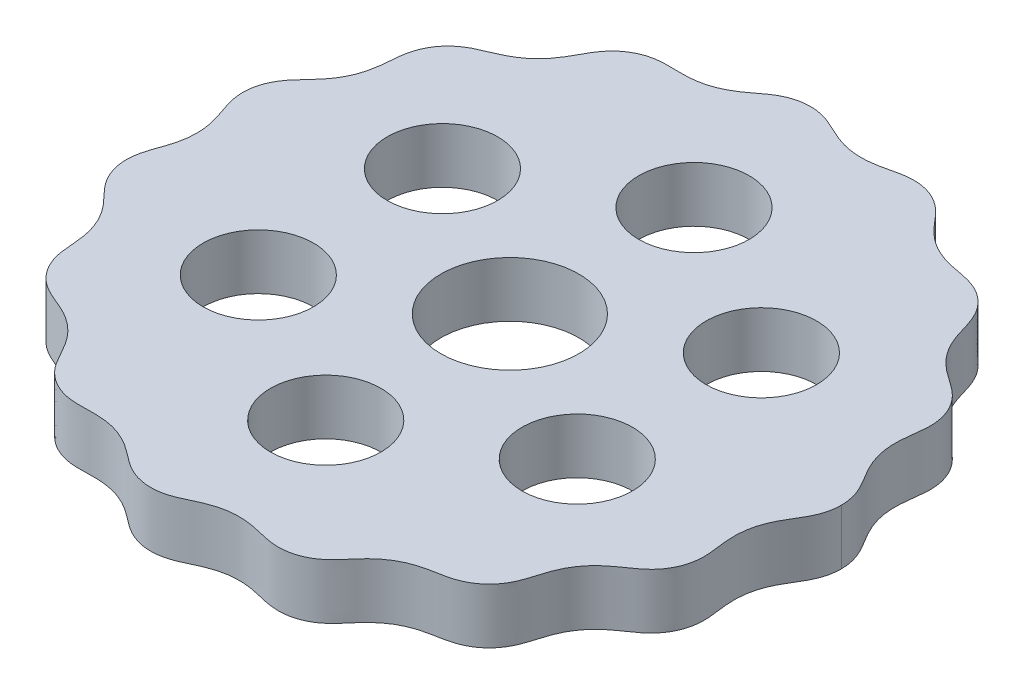
SolidWorks part; units mm, degrees
ref_plane "Front Plane" through (0, 0, 0) normal (0, 0, 1) x (1, 0, 0)
ref_plane "Top Plane" through (0, 0, 0) normal (0, 1, 0) x (1, 0, 0)
ref_plane "Right Plane" through (0, 0, 0) normal (1, 0, 0) x (0, 0, -1)
sketch "Sketch3" plane through (0, 0, 0) normal (0, 1, 0) x (1, 0, 0)
  line L0 (-55, 0) -> (55, 0) construction
  spline S2 degree 4 poles (-35, 0) (-35, -0.0358) (-35.0006, -0.1075) (-35.0034, -0.2568) (-35.0108, -0.4216) (-35.0218, -0.5882) (-35.0365, -0.7567) (-35.0593, -0.9658) (-35.104, -1.2906) (-35.1852, -1.7284) (-35.3211, -2.2743) (-35.5114, -2.8829) (-35.7441, -3.5419) (-35.9992, -4.258) (-36.256, -5.1614) (-36.3903, -6.2748) (-36.277, -7.5121) (-35.8687, -8.6952) (-35.2773, -9.6694) (-34.5543, -10.5199) (-33.7836, -11.2989) (-32.9858, -12.2016) (-32.2646, -13.303) (-31.7377, -14.5286) (-31.4262, -15.8454) (-31.2991, -17.2726) (-31.2161, -18.7053) (-30.8161, -20.1006) (-30.0732, -21.3418) (-29.1744, -22.2504) (-28.1724, -22.8961) (-27.1276, -23.3559) (-26.1086, -23.7587) (-25.0498, -24.278) (-23.9897, -24.9979) (-23.0387, -25.9222) (-22.2349, -27.0329) (-21.57, -28.2819) (-20.9001, -29.5134) (-19.9625, -30.5741) (-18.7952, -31.3663) (-17.5956, -31.8107) (-16.4147, -31.9743) (-15.2812, -31.959) (-14.2035, -31.9175) (-13.0422, -31.968) (-11.7833, -32.2012) (-10.5313, -32.6697) (-9.484, -33.2925) (-8.6483, -33.9206) (-7.824, -34.5602) (-6.9633, -35.1551) (-5.8447, -35.655) (-4.4715, -35.8938) (-3.1871, -35.8055) (-2.026, -35.4617) (-0.9923, -34.9762) (-0.0227, -34.5029) (1.0531, -34.0876) (2.2996, -33.7945) (3.6433, -33.7224) (5.0385, -33.8989) (6.246, -34.2125) (7.2644, -34.4441) (8.3052, -34.5433) (9.3521, -34.4822) (10.5168, -34.1673) (11.6593, -33.5372) (12.5907, -32.7091) (13.341, -31.8149) (14.0543, -30.9824) (14.885, -30.183) (15.9219, -29.4318) (16.9904, -28.9178) (18.0263, -28.6023) (18.918, -28.4136) (19.5788, -28.294) (20.4038, -28.1355) (21.3777, -27.8617) (22.444, -27.3351) (23.4837, -26.4602) (24.2541, -25.4059) (24.7506, -24.2626) (25.0639, -23.1466) (25.3786, -22.114) (25.8131, -21.0649) (26.4604, -19.9607) (27.3438, -18.9326) (28.3229, -18.1436) (29.2182, -17.5418) (30.0287, -16.9727) (30.7971, -16.3286) (31.5499, -15.4136) (32.138, -14.1887) (32.4089, -12.902) (32.389, -11.6377) (32.2136, -10.4744) (32.0853, -9.3852) (32.0701, -8.4106) (32.1519, -7.5639) (32.3146, -6.756) (32.5488, -5.9926) (32.8579, -5.2665) (33.2246, -4.5794) (33.5887, -3.9735) (33.9236, -3.4333) (34.2476, -2.8753) (34.5352, -2.2866) (34.722, -1.7814) (34.8335, -1.3753) (34.8947, -1.0872) (34.9248, -0.9216) (34.9499, -0.7552) (34.9676, -0.6083) (34.9796, -0.4838) (34.9875, -0.3802) (34.9925, -0.2949) (34.9973, -0.1832) (34.9994, -0.0895) (35, -0.0358) (35, 0) knots 0.07237 0.07237 0.07237 0.07237 0.07237 0.073615 0.074861 0.076106 0.077352 0.078597 0.079843 0.082334 0.087049 0.091763 0.096478 0.101193 0.107725 0.114257 0.124215 0.134174 0.144133 0.15093 0.157727 0.167143 0.176558 0.186521 0.196482 0.206428 0.216375 0.228908 0.238867 0.248826 0.258784 0.266347 0.27391 0.282559 0.291208 0.301173 0.311645 0.3216 0.331555 0.343059 0.353018 0.362977 0.372935 0.380513 0.388091 0.396475 0.404859 0.414823 0.425824 0.43578 0.440758 0.445737 0.45671 0.466668 0.476627 0.486585 0.494428 0.502271 0.510391 0.51851 0.528475 0.540003 0.54996 0.559918 0.565389 0.570861 0.580819 0.590778 0.600736 0.609095 0.617453 0.625308 0.633162 0.643126 0.655188 0.660155 0.665121 0.670088 0.675054 0.685012 0.69497 0.704929 0.714887 0.72326 0.731632 0.739222 0.746812 0.756777 0.769366 0.779036 0.78387 0.788705 0.798662 0.808621 0.81858 0.828538 0.837175 0.845812 0.853389 0.860965 0.865947 0.870929 0.877739 0.88455 0.889251 0.893953 0.898654 0.903356 0.908335 0.913314 0.914559 0.915803 0.917048 0.918293 0.919538 0.92016 0.920783 0.921405 0.922028 0.923272 0.923272 0.923272 0.923272 0.923272
  spline S3 degree 4 poles (-35, 0) (-35, 0.0358) (-35.0006, 0.1075) (-35.0034, 0.2568) (-35.0108, 0.4216) (-35.0218, 0.5882) (-35.0365, 0.7567) (-35.0593, 0.9658) (-35.104, 1.2906) (-35.1852, 1.7284) (-35.3211, 2.2743) (-35.5114, 2.8829) (-35.7441, 3.5419) (-35.9992, 4.258) (-36.256, 5.1614) (-36.3903, 6.2748) (-36.277, 7.5121) (-35.8687, 8.6952) (-35.2773, 9.6694) (-34.5543, 10.5199) (-33.7836, 11.2989) (-32.9858, 12.2016) (-32.2646, 13.303) (-31.7377, 14.5286) (-31.4262, 15.8454) (-31.2991, 17.2726) (-31.2161, 18.7053) (-30.8161, 20.1006) (-30.0732, 21.3418) (-29.1744, 22.2504) (-28.1724, 22.8961) (-27.1276, 23.3559) (-26.1086, 23.7587) (-25.0498, 24.278) (-23.9897, 24.9979) (-23.0387, 25.9222) (-22.2349, 27.0329) (-21.57, 28.2819) (-20.9001, 29.5134) (-19.9625, 30.5741) (-18.7952, 31.3663) (-17.5956, 31.8107) (-16.4147, 31.9743) (-15.2812, 31.959) (-14.2035, 31.9175) (-13.0422, 31.968) (-11.7833, 32.2012) (-10.5313, 32.6697) (-9.484, 33.2925) (-8.6483, 33.9206) (-7.824, 34.5602) (-6.9633, 35.1551) (-5.8447, 35.655) (-4.4715, 35.8938) (-3.1871, 35.8055) (-2.026, 35.4617) (-0.9923, 34.9762) (-0.0227, 34.5029) (1.0531, 34.0876) (2.2996, 33.7945) (3.6433, 33.7224) (5.0385, 33.8989) (6.246, 34.2125) (7.2644, 34.4441) (8.3052, 34.5433) (9.3521, 34.4822) (10.5168, 34.1673) (11.6593, 33.5372) (12.5907, 32.7091) (13.341, 31.8149) (14.0543, 30.9824) (14.885, 30.183) (15.9219, 29.4318) (16.9904, 28.9178) (18.0263, 28.6023) (18.918, 28.4136) (19.5788, 28.294) (20.4038, 28.1355) (21.3777, 27.8617) (22.444, 27.3351) (23.4837, 26.4602) (24.2541, 25.4059) (24.7506, 24.2626) (25.0639, 23.1466) (25.3786, 22.114) (25.8131, 21.0649) (26.4604, 19.9607) (27.3438, 18.9326) (28.3229, 18.1436) (29.2182, 17.5418) (30.0287, 16.9727) (30.7971, 16.3286) (31.5499, 15.4136) (32.138, 14.1887) (32.4089, 12.902) (32.389, 11.6377) (32.2136, 10.4744) (32.0853, 9.3852) (32.0701, 8.4106) (32.1519, 7.5639) (32.3146, 6.756) (32.5488, 5.9926) (32.8579, 5.2665) (33.2246, 4.5794) (33.5887, 3.9735) (33.9236, 3.4333) (34.2476, 2.8753) (34.5352, 2.2866) (34.722, 1.7814) (34.8335, 1.3753) (34.8947, 1.0872) (34.9248, 0.9216) (34.9499, 0.7552) (34.9676, 0.6083) (34.9796, 0.4838) (34.9875, 0.3802) (34.9925, 0.2949) (34.9973, 0.1832) (34.9994, 0.0895) (35, 0.0358) (35, 0) knots 0.07237 0.07237 0.07237 0.07237 0.07237 0.073615 0.074861 0.076106 0.077352 0.078597 0.079843 0.082334 0.087049 0.091763 0.096478 0.101193 0.107725 0.114257 0.124215 0.134174 0.144133 0.15093 0.157727 0.167143 0.176558 0.186521 0.196482 0.206428 0.216375 0.228908 0.238867 0.248826 0.258784 0.266347 0.27391 0.282559 0.291208 0.301173 0.311645 0.3216 0.331555 0.343059 0.353018 0.362977 0.372935 0.380513 0.388091 0.396475 0.404859 0.414823 0.425824 0.43578 0.440758 0.445737 0.45671 0.466668 0.476627 0.486585 0.494428 0.502271 0.510391 0.51851 0.528475 0.540003 0.54996 0.559918 0.565389 0.570861 0.580819 0.590778 0.600736 0.609095 0.617453 0.625308 0.633162 0.643126 0.655188 0.660155 0.665121 0.670088 0.675054 0.685012 0.69497 0.704929 0.714887 0.72326 0.731632 0.739222 0.746812 0.756777 0.769366 0.779036 0.78387 0.788705 0.798662 0.808621 0.81858 0.828538 0.837175 0.845812 0.853389 0.860965 0.865947 0.870929 0.877739 0.88455 0.889251 0.893953 0.898654 0.903356 0.908335 0.913314 0.914559 0.915803 0.917048 0.918293 0.919538 0.92016 0.920783 0.921405 0.922028 0.923272 0.923272 0.923272 0.923272 0.923272
extrude "Boss-Extrude1" add sketch "Sketch3" along normal blind 6
sketch "Sketch4" plane through (0, 6, 0) normal (0, 1, 0) x (1, 0, 0)
  circle A0 centre (-1, 0) radius 7.5
  circle A1 centre (-1, 0) radius 20 construction
  circle A2 centre (-1, 20) radius 6
  circle A3 centre (16.3205, 10) radius 6
  circle A4 centre (16.3205, -10) radius 6
  circle A5 centre (-1, -20) radius 6
  circle A6 centre (-18.3205, -10) radius 6
  circle A7 centre (-18.3205, 10) radius 6
  point P19 (-1, 0)
  dimension "D1" = 15
  dimension "D2" = 40
  dimension "D3" = 12
  dimension "D5" = 1
  dimension "D4" = 6
extrude "Cut-Extrude1" cut sketch "Sketch4" against normal through all
equation "\"R_SUN\"= 40"
equation "\"R_ROLL\"= 5"
equation "\"GRATIO\"= 15"
equation "\"RHO\"= 1"
